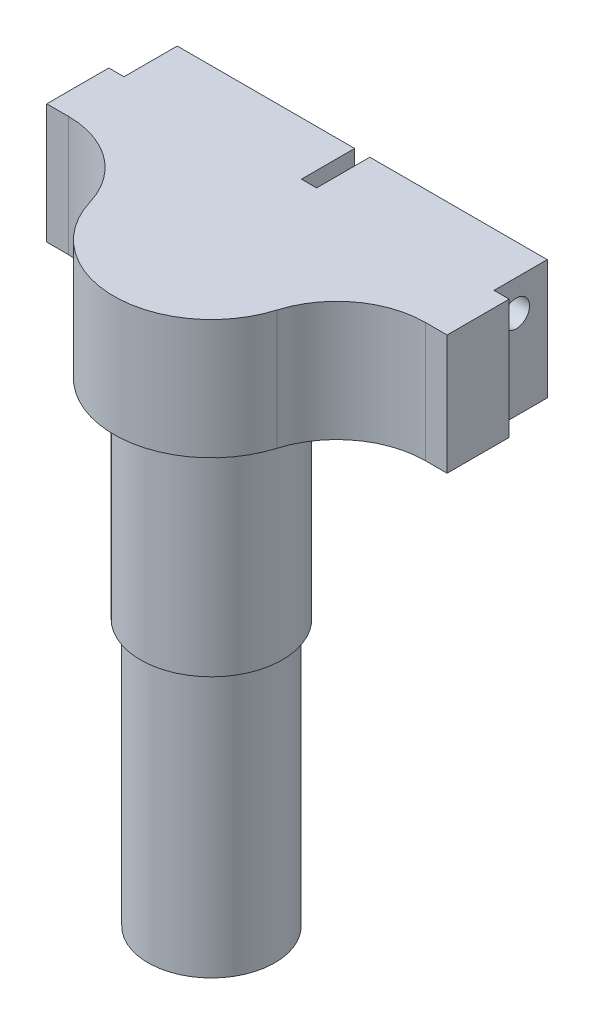
SolidWorks part; units mm, degrees
ref_plane "Front Plane" through (0, 0, 0) normal (0, 0, 1) x (1, 0, 0)
ref_plane "Top Plane" through (0, 0, 0) normal (0, 1, 0) x (1, 0, 0)
ref_plane "Right Plane" through (0, 0, 0) normal (1, 0, 0) x (0, 0, -1)
sketch "Sketch1" plane through (0, 0, 0) normal (0, 1, 0) x (1, 0, 0)
  line L0 (0, 0) -> (45.13, 0)
  line L1 (0, 0) -> (22.565, 0)
  line L2 (22.565, 0) -> (22.565, -8)
  line L3 (0, 0) -> (0, 7)
  line L4 (0, 7) -> (45.13, 7)
  line L5 (45.13, 7) -> (45.13, 0)
  circle A2 centre (22.565, -8) radius 11
  circle A3 centre (22.565, -8) radius 8
extrude "Boss-Extrude1" add sketch "Sketch1" along normal blind 10 contours A2 L0 L5 L4 L3 | L0 A2 L1 | A3 L1 A2 L0
sketch "Sketch2" plane through (0, 10, 0) normal (0, 1, 0) x (1, 0, 0)
  line L0 (0, 7) -> (1.71, 7)
  line L1 (0, 7) -> (45.13, 7) construction
  line L2 (1.71, 7) -> (21.71, 7)
  line L3 (21.71, 7) -> (23.42, 7)
  line L4 (23.42, 7) -> (43.42, 7)
  line L5 (43.42, 7) -> (45.13, 7)
  line L6 (0, 0) -> (0, 3)
  line L7 (0, 0) -> (0, 7) construction
  line L8 (0, 3) -> (45.13, 3)
  line L9 (45.13, 7) -> (45.13, 0) construction
  line L10 (1.71, 7) -> (1.71, 3)
  line L11 (1.71, 3) -> (21.71, 3)
  line L12 (21.71, 3) -> (21.71, 7)
  line L13 (23.42, 7) -> (23.42, 3)
  line L14 (23.42, 3) -> (43.42, 3)
  line L15 (43.42, 3) -> (43.42, 7)
  line L16 (0, 7) -> (0, 3)
  line L17 (45.13, 3) -> (45.13, 7)
  line M7 (45.13, 0) -> (45.13, 7)
  line M8 (45.13, 7) -> (0, 7)
  line M9 (0, 7) -> (0, 0)
extrude "Cut-Extrude1" cut sketch "Sketch2" against normal blind 10 contours L10 L8 M8 M9 | L13 L12 L8 M8 | L15 L8 M7 M8
sketch "Sketch3" plane through (0, 0, -7) normal (0, 0, -1) x (-1, 0, 0)
  line L0 (-43.42, 0) -> (-23.42, 0) construction
  line L1 (-23.42, 0) -> (-23.42, 10) construction
  line L2 (-23.42, 10) -> (-43.42, 10) construction
  line L3 (-43.42, 10) -> (-43.42, 0) construction
  line L4 (-21.71, 0) -> (-1.71, 0) construction
  line L5 (-1.71, 0) -> (-1.71, 10) construction
  line L6 (-1.71, 10) -> (-21.71, 10) construction
  line L7 (-21.71, 10) -> (-21.71, 0) construction
  line L8 (-43.42, 0) -> (-23.42, 0)
  line L9 (-23.42, 0) -> (-23.42, 10)
  line L10 (-23.42, 10) -> (-43.42, 10)
  line L11 (-43.42, 10) -> (-43.42, 0)
  line L12 (-21.71, 0) -> (-1.71, 0)
  line L13 (-1.71, 0) -> (-1.71, 10)
  line L14 (-1.71, 10) -> (-21.71, 10)
  line L15 (-21.71, 10) -> (-21.71, 0)
extrude "Boss-Extrude2" add sketch "Sketch3" along normal blind 3
sketch "Sketch4" plane through (0, 10, 0) normal (0, 1, 0) x (1, 0, 0)
  line L13 (21.71, 3) -> (21.71, 10)
  line L14 (21.71, 10) -> (1.71, 10)
  line L15 (1.71, 10) -> (1.71, 3)
  line L16 (1.71, 3) -> (0, 3)
  line L17 (0, 3) -> (0, 0)
  line L18 (0, 0) -> (15.0152, 0)
  line L19 (30.1148, 0) -> (45.13, 0)
  line L20 (45.13, 0) -> (45.13, 3)
  line L21 (45.13, 3) -> (43.42, 3)
  line L22 (43.42, 3) -> (43.42, 10)
  line L23 (43.42, 10) -> (23.42, 10)
  line L24 (23.42, 10) -> (23.42, 3)
  line L25 (23.42, 3) -> (21.71, 3)
  line L26 (21.71, 3) -> (21.71, 10)
  line L27 (21.71, 10) -> (1.71, 10)
  line L28 (1.71, 10) -> (1.71, 3)
  line L29 (1.71, 3) -> (0, 3)
  line L30 (0, 3) -> (0, 0)
  line L31 (0, 0) -> (15.0152, 0)
  line L32 (30.1148, 0) -> (45.13, 0)
  line L33 (45.13, 0) -> (45.13, 3)
  line L34 (45.13, 3) -> (43.42, 3)
  line L35 (43.42, 3) -> (43.42, 10)
  line L36 (43.42, 10) -> (23.42, 10)
  line L37 (23.42, 10) -> (23.42, 3)
  line L38 (23.42, 3) -> (21.71, 3)
  arc A4 (15.0152, 0) -> (30.1148, 0) centre (22.565, -8) ccw
  arc A7 (15.0152, 0) -> (30.1148, 0) centre (22.565, -8) ccw
  dimension "D1" = 0
extrude "Cut-Extrude2" cut sketch "Sketch4" against normal blind 3
sketch "Sketch6" plane through (0, 0, -10) normal (0, 0, -1) x (-1, 0, 0)
  line L0 (-23.42, 0) -> (-23.42, 7) construction
  line L1 (-23.42, 7) -> (-43.42, 7) construction
  line L2 (-43.42, 7) -> (-43.42, 0) construction
  line L3 (-43.42, 0) -> (-23.42, 0) construction
  line L4 (-1.71, 0) -> (-1.71, 7) construction
  line L5 (-1.71, 7) -> (-21.71, 7) construction
  line L6 (-21.71, 7) -> (-21.71, 0) construction
  line L7 (-21.71, 0) -> (-1.71, 0) construction
  line L8 (-23.42, 0) -> (-23.42, 7)
  line L9 (-23.42, 7) -> (-43.42, 7)
  line L10 (-43.42, 7) -> (-43.42, 0)
  line L11 (-43.42, 0) -> (-23.42, 0)
  line L12 (-1.71, 0) -> (-1.71, 7)
  line L13 (-1.71, 7) -> (-21.71, 7)
  line L14 (-21.71, 7) -> (-21.71, 0)
  line L15 (-21.71, 0) -> (-1.71, 0)
extrude "Boss-Extrude3" add sketch "Sketch6" along normal blind 2
sketch "Sketch7" plane through (1.71, 0, 0) normal (-1, 0, 0) x (0, 0, 1)
  line L0 (-3, 0) -> (-3, 7)
  line L1 (-3, 7) -> (-3, 3.5)
  line L2 (-3, 3.5) -> (-8.5, 3.5)
  circle A0 centre (-8.5, 3.5) radius 1.5
extrude "Cut-Extrude5" cut sketch "Sketch7" against normal blind 44
sketch "Sketch9" plane through (0, 0, -3) normal (0, 0, -1) x (-1, 0, 0)
  line L4 (-21.71, 7) -> (-23.42, 7)
  line L5 (-23.42, 7) -> (-23.42, 0)
  line L6 (-23.42, 0) -> (-21.71, 0)
  line L7 (-21.71, 0) -> (-21.71, 7)
  line L8 (-21.71, 7) -> (-23.42, 7)
  line L9 (-23.42, 7) -> (-23.42, 0)
  line L10 (-23.42, 0) -> (-21.71, 0)
  line L11 (-21.71, 0) -> (-21.71, 7)
  line L12 (0, 7) -> (-1.71, 7)
  line L13 (-1.71, 7) -> (-1.71, 0)
  line L14 (-1.71, 0) -> (0, 0)
  line L15 (0, 0) -> (0, 7)
  line L16 (0, 7) -> (-1.71, 7)
  line L17 (-1.71, 7) -> (-1.71, 0)
  line L18 (-1.71, 0) -> (0, 0)
  line L19 (0, 0) -> (0, 7)
  line L20 (-43.42, 7) -> (-45.13, 7)
  line L21 (-45.13, 7) -> (-45.13, 0)
  line L22 (-45.13, 0) -> (-43.42, 0)
  line L23 (-43.42, 0) -> (-43.42, 7)
  line L24 (-43.42, 7) -> (-45.13, 7)
  line L25 (-45.13, 7) -> (-45.13, 0)
  line L26 (-45.13, 0) -> (-43.42, 0)
  line L27 (-43.42, 0) -> (-43.42, 7)
  dimension "D1" = 0
  dimension "D2" = 0
  dimension "D3" = 0
extrude "Boss-Extrude4" add sketch "Sketch9" along normal blind 3
sketch "Sketch11" plane through (0, 7, 0) normal (0, 1, 0) x (1, 0, 0)
  line L13 (45.13, 6) -> (43.42, 6)
  line L14 (43.42, 6) -> (43.42, 12)
  line L15 (43.42, 12) -> (23.42, 12)
  line L16 (23.42, 12) -> (23.42, 6)
  line L17 (23.42, 6) -> (21.71, 6)
  line L18 (21.71, 6) -> (21.71, 12)
  line L19 (21.71, 12) -> (1.71, 12)
  line L20 (1.71, 12) -> (1.71, 6)
  line L21 (1.71, 6) -> (0, 6)
  line L22 (0, 6) -> (0, 0)
  line L23 (0, 0) -> (15.0152, 0)
  line L24 (30.1148, 0) -> (45.13, 0)
  line L25 (45.13, 0) -> (45.13, 6)
  line L26 (45.13, 6) -> (43.42, 6)
  line L27 (43.42, 6) -> (43.42, 12)
  line L28 (43.42, 12) -> (23.42, 12)
  line L29 (23.42, 12) -> (23.42, 6)
  line L30 (23.42, 6) -> (21.71, 6)
  line L31 (21.71, 6) -> (21.71, 12)
  line L32 (21.71, 12) -> (1.71, 12)
  line L33 (1.71, 12) -> (1.71, 6)
  line L34 (1.71, 6) -> (0, 6)
  line L35 (0, 6) -> (0, 0)
  line L36 (0, 0) -> (15.0152, 0)
  line L37 (30.1148, 0) -> (45.13, 0)
  line L38 (45.13, 0) -> (45.13, 6)
  circle A0 centre (22.565, -8) radius 8 construction
  circle A1 centre (22.565, -8) radius 8
  arc A4 (15.0152, 0) -> (30.1148, 0) centre (22.565, -8) ccw
  arc A7 (15.0152, 0) -> (30.1148, 0) centre (22.565, -8) ccw
  dimension "D1" = 0
extrude "Cut-Extrude6" cut sketch "Sketch11" against normal blind 1
sketch "Sketch12" plane through (0, 6, 0) normal (0, 1, 0) x (1, 0, 0)
  line L13 (45.13, 0) -> (45.13, 6)
  line L14 (45.13, 6) -> (43.42, 6)
  line L15 (43.42, 6) -> (43.42, 12)
  line L16 (43.42, 12) -> (23.42, 12)
  line L17 (23.42, 12) -> (23.42, 6)
  line L18 (23.42, 6) -> (21.71, 6)
  line L19 (21.71, 6) -> (21.71, 12)
  line L20 (21.71, 12) -> (1.71, 12)
  line L21 (1.71, 12) -> (1.71, 6)
  line L22 (1.71, 6) -> (0, 6)
  line L23 (0, 6) -> (0, 0)
  line L24 (0, 0) -> (15.0152, 0)
  line L25 (30.1148, 0) -> (45.13, 0)
  line L26 (45.13, 0) -> (45.13, 6)
  line L27 (45.13, 6) -> (43.42, 6)
  line L28 (43.42, 6) -> (43.42, 12)
  line L29 (43.42, 12) -> (23.42, 12)
  line L30 (23.42, 12) -> (23.42, 6)
  line L31 (23.42, 6) -> (21.71, 6)
  line L32 (21.71, 6) -> (21.71, 12)
  line L33 (21.71, 12) -> (1.71, 12)
  line L34 (1.71, 12) -> (1.71, 6)
  line L35 (1.71, 6) -> (0, 6)
  line L36 (0, 6) -> (0, 0)
  line L37 (0, 0) -> (15.0152, 0)
  line L38 (30.1148, 0) -> (45.13, 0)
  arc A4 (15.0152, 0) -> (30.1148, 0) centre (22.565, -8) ccw
  arc A7 (15.0152, 0) -> (30.1148, 0) centre (22.565, -8) ccw
  dimension "D1" = 0
extrude "Boss-Extrude6" add sketch "Sketch12" along normal blind 1
sketch "Sketch13" plane through (0, 6, 0) normal (0, -1, 0) x (1, 0, 0)
  circle A1 centre (22.565, 8) radius 8
  circle A2 centre (22.565, 8) radius 8
  dimension "D1" = 0
extrude "Boss-Extrude7" add sketch "Sketch13" along normal up to surface (6 mm away) up to face at (22.565, 0, -4.6429)
sketch "Sketch14" plane through (0, 0, 0) normal (0, -1, 0) x (1, 0, 0)
  circle A0 centre (22.565, 8) radius 8
extrude "Boss-Extrude8" add sketch "Sketch14" along normal blind 40
sketch "Sketch15" plane through (0, -40, 0) normal (0, -1, 0) x (1, 0, 0)
  circle A0 centre (22.565, 8) radius 7.5
extrude "Boss-Extrude9" add sketch "Sketch15" along normal blind 30
sketch "Sketch16" plane through (0, 0, 0) normal (0, -1, 0) x (1, 0, 0)
  line L13 (43.42, -12) -> (43.42, -6)
  line L14 (43.42, -6) -> (45.13, -6)
  line L15 (45.13, -6) -> (45.13, 0)
  line L16 (45.13, 0) -> (30.1148, 0)
  line L17 (15.0152, 0) -> (0, 0)
  line L18 (0, 0) -> (0, -6)
  line L19 (0, -6) -> (1.71, -6)
  line L20 (1.71, -6) -> (1.71, -12)
  line L21 (1.71, -12) -> (21.71, -12)
  line L22 (21.71, -12) -> (21.71, -6)
  line L23 (21.71, -6) -> (23.42, -6)
  line L24 (23.42, -6) -> (23.42, -12)
  line L25 (23.42, -12) -> (43.42, -12)
  line L26 (43.42, -12) -> (43.42, -6)
  line L27 (43.42, -6) -> (45.13, -6)
  line L28 (45.13, -6) -> (45.13, 0)
  line L29 (45.13, 0) -> (30.1148, 0)
  line L30 (15.0152, 0) -> (0, 0)
  line L31 (0, 0) -> (0, -6)
  line L32 (0, -6) -> (1.71, -6)
  line L33 (1.71, -6) -> (1.71, -12)
  line L34 (1.71, -12) -> (21.71, -12)
  line L35 (21.71, -12) -> (21.71, -6)
  line L36 (21.71, -6) -> (23.42, -6)
  line L37 (23.42, -6) -> (23.42, -12)
  line L38 (23.42, -12) -> (43.42, -12)
  arc A4 (30.1148, 0) -> (15.0152, 0) centre (22.565, 8) ccw
  arc A7 (30.1148, 0) -> (15.0152, 0) centre (22.565, 8) ccw
  dimension "D1" = 0
extrude "Boss-Extrude10" add sketch "Sketch16" along normal blind 6.5
sketch "Sketch17" plane through (0, -70, 0) normal (0, -1, 0) x (1, 0, 0)
  circle A0 centre (22.565, 8) radius 7
  circle A1 centre (22.565, 8) radius 15.7734
extrude "Cut-Extrude7" cut sketch "Sketch17" against normal up to surface (30 mm away) up to face at (22.565, -40, 0.5)
sketch "Sketch18" plane through (0, -70, 0) normal (0, -1, 0) x (1, 0, 0)
  circle A0 centre (22.565, 8) radius 7.1
extrude "Boss-Extrude11" add sketch "Sketch18" against normal up to surface (30 mm away) contours A0 up to face at (22.565, -40, 0)
sketch "Sketch19" plane through (0, -70, 0) normal (0, -1, 0) x (1, 0, 0)
  circle A0 centre (22.565, 8) radius 7.2
extrude "Boss-Extrude12" add sketch "Sketch19" against normal up to surface (30 mm away) up to face at (22.565, -40, 0.9)
sketch "Sketch20" plane through (0, -70, 0) normal (0, -1, 0) x (1, 0, 0)
  circle A0 centre (22.565, 8) radius 7.15
  circle A1 centre (22.565, 8) radius 12.8107
extrude "Cut-Extrude8" cut sketch "Sketch20" against normal up to surface (30 mm away) up to face at (22.565, -40, 0.8)
sketch "Sketch21" plane through (0, -70, 0) normal (0, -1, 0) x (1, 0, 0)
  circle A1 centre (22.565, 8) radius 7.15
  circle A2 centre (22.565, 8) radius 7.15
  dimension "D1" = 0
extrude "Cut-Extrude9" cut sketch "Sketch21" against normal blind 10
sketch "Sketch22" plane through (0, -40, 0) normal (0, -1, 0) x (1, 0, 0)
  circle A0 centre (22.565, 8) radius 7.15 construction
  circle A1 centre (22.565, 8) radius 8 construction
  circle A2 centre (22.565, 8) radius 7.15
  circle A3 centre (22.565, 8) radius 8
extrude "Cut-Extrude10" cut sketch "Sketch22" against normal blind 10
sketch "Sketch25" plane through (0, 7, 0) normal (0, 1, 0) x (1, 0, 0)
  line L0 (0, 6) -> (0, 3)
  line L1 (0, 6) -> (0, 0) construction
  line L2 (0, 3) -> (45.13, 3)
  line L3 (45.13, 0) -> (45.13, 6) construction
  line L4 (1.71, 6) -> (1.71, 3)
  line L5 (21.71, 6) -> (21.71, 3)
  line L6 (23.42, 6) -> (23.42, 3)
  line L7 (43.42, 6) -> (43.42, 3)
  line L8 (0, 6) -> (45.13, 6)
  line L9 (45.13, 6) -> (45.13, 3)
  line L10 (1.71, 12) -> (1.71, 9)
  line L11 (1.71, 12) -> (1.71, 6) construction
  line L12 (1.71, 9) -> (43.42, 9)
  line L13 (43.42, 6) -> (43.42, 12) construction
  line L14 (43.42, 9) -> (43.42, 12)
  line L15 (43.42, 12) -> (1.71, 12)
  circle A0 centre (22.565, -8) radius 8
  line M2 (45.13, 0) -> (45.13, 6)
  line M3 (45.13, 6) -> (43.42, 6)
  line M4 (43.42, 6) -> (43.42, 12)
  line M5 (43.42, 12) -> (23.42, 12)
  line M6 (23.42, 12) -> (23.42, 6)
  line M7 (23.42, 6) -> (21.71, 6)
  line M8 (21.71, 6) -> (21.71, 12)
  line M9 (21.71, 12) -> (1.71, 12)
  line M10 (1.71, 12) -> (1.71, 6)
  line M11 (1.71, 6) -> (0, 6)
  line M12 (0, 6) -> (0, 0)
extrude "Cut-Extrude13" cut sketch "Sketch25" against normal blind 21 contours L4 L2 M11 M12 | L12 M10 M8 M9 | L12 M6 M4 M5 | L6 L5 L2 M7 | L7 L2 M3 M2
sketch "Sketch26" plane through (1.71, 0, 0) normal (-1, 0, 0) x (0, 0, 1)
  line L0 (-3, 7) -> (-6, 7)
  line L1 (-9, 7) -> (-3, 7) construction
  line L2 (-9, 7) -> (-9, -6.5)
  circle A0 centre (-8.5, 3.5) radius 1.5
  arc M7 (-9, 4.9142) -> (-9, 2.0858) centre (-8.5, 3.5) cw
extrude "Boss-Extrude13" add sketch "Sketch26" against normal up to surface (20 mm away) contours L2 M7 up to face at (21.71, 1.3333, -6.6667)
sketch "Sketch27" plane through (43.42, 0, 0) normal (1, 0, 0) x (0, 0, -1)
  line L0 (9, 7) -> (9, -6.5)
  circle A1 centre (8.5, 3.5) radius 1.5
  arc M7 (9, 2.0858) -> (9, 4.9142) centre (8.5, 3.5) cw
extrude "Boss-Extrude14" add sketch "Sketch27" against normal up to surface (20 mm away) contours L0 M7 up to face at (23.42, 1.3333, -6.6667)
sketch "Sketch28" plane through (1.71, 0, 0) normal (-1, 0, 0) x (0, 0, 1)
  line L2 (-3, 7) -> (-3, 3.5)
  line L3 (-3, -6.5) -> (-3, 7) construction
  line L4 (-3, 3.5) -> (-5.5, 3.5)
  circle A0 centre (-5.5, 3.5) radius 1.5
extrude "Cut-Extrude14" cut sketch "Sketch28" against normal blind 50
sketch "Sketch29" plane through (0, 0, 0) normal (0, 0, 1) x (1, 0, 0)
  line L0 (0, 7) -> (0, -6.5)
  line L1 (0, -6.5) -> (45.13, -6.5)
  line L2 (45.13, -6.5) -> (45.13, 7)
  line L3 (45.13, 7) -> (0, 7)
extrude "Boss-Extrude15" add sketch "Sketch29" along normal blind 4
fillet "Fillet1" radius 10 2 edges at (12.318, 0.25, 4) (32.812, 0.25, 4)
fillet "Fillet2" radius 2 1 edges at (22.565, -6.5, 0)
